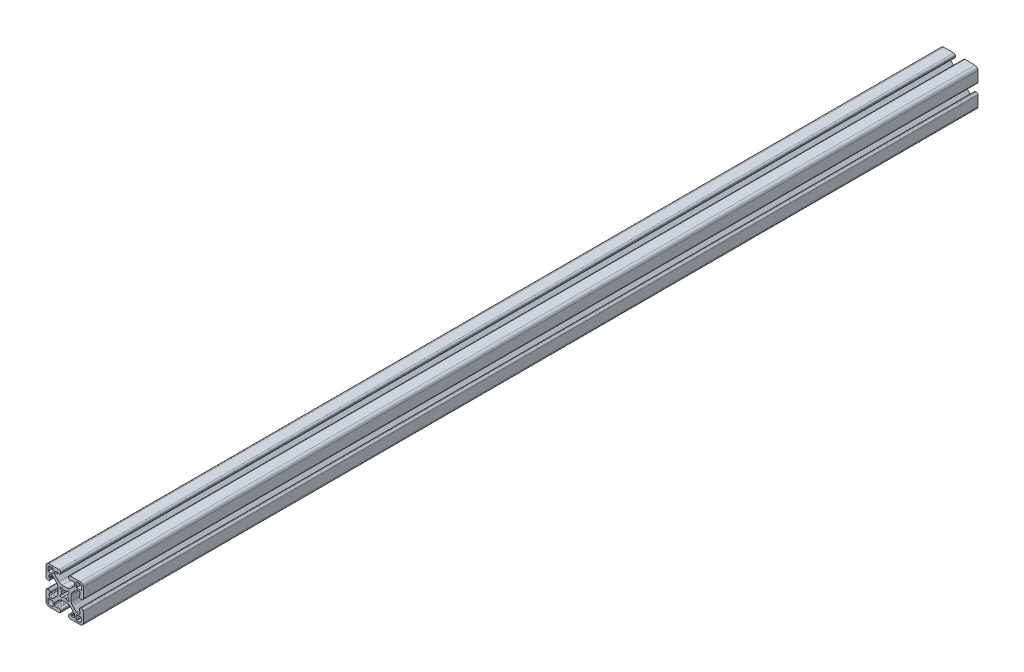
SolidWorks part; units mm, degrees
ref_plane "Front Plane" through (0, 0, 0) normal (0, 0, 1) x (1, 0, 0)
ref_plane "Top Plane" through (0, 0, 0) normal (0, 1, 0) x (1, 0, 0)
ref_plane "Right Plane" through (0, 0, 0) normal (1, 0, 0) x (0, 0, -1)
sketch "Sketch1" plane through (0, 0, 0) normal (0, 0, 1) x (1, 0, 0)
  line L0 (-66.7042, -2.4885) -> (-65.3338, -1.1181)
  line L1 (-65.3338, 1.5948) -> (-66.7042, 2.9652)
  line L2 (-65.0878, 4.5817) -> (-63.7174, 3.2112)
  line L3 (-61.0045, 3.2112) -> (-59.7212, 4.484)
  line L4 (-58.1153, 2.8781) -> (-59.388, 1.5948)
  line L5 (-59.388, -1.1181) -> (-58.0176, -2.4885)
  line L6 (-59.6341, -4.1049) -> (-61.0045, -2.7345)
  line L7 (-63.7174, -2.7345) -> (-65.0878, -4.1049)
  line L8 (-79.6076, 12.4812) -> (-79.6076, 14.691)
  line L9 (-76.8136, 17.485) -> (-74.6038, 17.485)
  line L10 (-74.2227, 17.1039) -> (-74.2227, 12.4812)
  line L11 (-74.6038, 12.1001) -> (-79.2265, 12.1001)
  line L12 (-74.6038, -17.0083) -> (-76.8136, -17.0083)
  line L13 (-79.6076, -14.2142) -> (-79.6076, -12.0045)
  line L14 (-79.2265, -11.6233) -> (-74.6038, -11.6233)
  line L15 (-74.2227, -12.0045) -> (-74.2227, -16.6272)
  line L16 (-45.1143, -12.0045) -> (-45.1143, -14.2142)
  line L17 (-47.9083, -17.0083) -> (-50.1181, -17.0083)
  line L18 (-50.4992, -16.6272) -> (-50.4992, -12.0045)
  line L19 (-50.1181, -11.6233) -> (-45.4954, -11.6233)
  line L20 (-50.1181, 17.485) -> (-47.9083, 17.485)
  line L21 (-45.1143, 14.691) -> (-45.1143, 12.4812)
  line L22 (-45.4954, 12.1001) -> (-50.1181, 12.1001)
  line L23 (-50.4992, 12.4812) -> (-50.4992, 17.1039)
  line L24 (-46.5366, -7.0008) -> (-46.5366, -8.778)
  line L25 (-47.8071, -10.0485) -> (-49.3926, -10.0485)
  line L26 (-50.291, -9.6763) -> (-54.2387, -5.7286)
  line L27 (-55.6299, -2.3699) -> (-55.6299, 2.8467)
  line L28 (-54.2387, 6.2053) -> (-50.291, 10.1531)
  line L29 (-49.3926, 10.5252) -> (-47.8071, 10.5252)
  line L30 (-46.5366, 9.2547) -> (-46.5366, 7.4775)
  line L31 (-46.9177, 7.0964) -> (-46.9939, 7.0964)
  line L32 (-47.375, 6.7153) -> (-47.375, 5.8772)
  line L33 (-45.8002, 4.3023) -> (-44.8858, 4.3023)
  line L34 (-43.3109, 5.8772) -> (-43.3109, 16.1134)
  line L35 (-46.4859, 19.2884) -> (-56.7221, 19.2884)
  line L36 (-58.297, 17.7135) -> (-58.297, 16.7991)
  line L37 (-56.7221, 15.2243) -> (-55.884, 15.2243)
  line L38 (-55.5029, 15.6054) -> (-55.5029, 15.6816)
  line L39 (-55.1218, 16.0627) -> (-53.3446, 16.0627)
  line L40 (-52.0741, 14.7922) -> (-52.0741, 13.2067)
  line L41 (-52.4462, 12.3083) -> (-56.394, 8.3605)
  line L42 (-59.7526, 6.9694) -> (-64.9692, 6.9694)
  line L43 (-68.3278, 8.3605) -> (-72.2756, 12.3083)
  line L44 (-72.6478, 13.2067) -> (-72.6478, 14.7922)
  line L45 (-71.3773, 16.0627) -> (-69.6001, 16.0627)
  line L46 (-69.219, 15.6816) -> (-69.219, 15.6054)
  line L47 (-68.8379, 15.2243) -> (-67.9997, 15.2243)
  line L48 (-66.4249, 16.7991) -> (-66.4249, 17.7135)
  line L49 (-67.9997, 19.2884) -> (-78.2359, 19.2884)
  line L50 (-81.4109, 16.1134) -> (-81.4109, 5.8772)
  line L51 (-79.8361, 4.3023) -> (-78.9217, 4.3023)
  line L52 (-77.3469, 5.8772) -> (-77.3469, 6.7153)
  line L53 (-77.728, 7.0964) -> (-77.8042, 7.0964)
  line L54 (-78.1853, 7.4775) -> (-78.1853, 9.2547)
  line L55 (-76.9148, 10.5252) -> (-75.3293, 10.5252)
  line L56 (-74.4309, 10.1531) -> (-70.4831, 6.2053)
  line L57 (-69.0919, 2.8467) -> (-69.0919, -2.3699)
  line L58 (-70.4831, -5.7286) -> (-74.4309, -9.6763)
  line L59 (-75.3293, -10.0485) -> (-76.9148, -10.0485)
  line L60 (-78.1853, -8.778) -> (-78.1853, -7.0008)
  line L61 (-77.8042, -6.6197) -> (-77.728, -6.6197)
  line L62 (-77.3469, -6.2386) -> (-77.3469, -5.4004)
  line L63 (-78.9217, -3.8256) -> (-79.8361, -3.8256)
  line L64 (-81.4109, -5.4004) -> (-81.4109, -15.6366)
  line L65 (-78.2359, -18.8117) -> (-67.9997, -18.8117)
  line L66 (-66.4249, -17.2368) -> (-66.4249, -16.3224)
  line L67 (-67.9997, -14.7476) -> (-68.8379, -14.7476)
  line L68 (-69.219, -15.1287) -> (-69.219, -15.2049)
  line L69 (-69.6001, -15.586) -> (-71.3773, -15.586)
  line L70 (-72.6478, -14.3155) -> (-72.6478, -12.73)
  line L71 (-72.2756, -11.8316) -> (-68.3278, -7.8838)
  line L72 (-64.9692, -6.4926) -> (-59.7526, -6.4926)
  line L73 (-56.394, -7.8838) -> (-52.4462, -11.8316)
  line L74 (-52.0741, -12.73) -> (-52.0741, -14.3155)
  line L75 (-53.3446, -15.586) -> (-55.1218, -15.586)
  line L76 (-55.5029, -15.2049) -> (-55.5029, -15.1287)
  line L77 (-55.884, -14.7476) -> (-56.7221, -14.7476)
  line L78 (-58.297, -16.3224) -> (-58.297, -17.2368)
  line L79 (-56.7221, -18.8117) -> (-46.4859, -18.8117)
  line L80 (-43.3109, -15.6366) -> (-43.3109, -5.4004)
  line L81 (-44.8858, -3.8256) -> (-45.8002, -3.8256)
  line L82 (-47.375, -5.4004) -> (-47.375, -6.2386)
  line L83 (-46.9939, -6.6197) -> (-46.9177, -6.6197)
  arc A0 (-66.7042, -2.4885) -> (-65.0878, -4.1049) centre (-65.896, -3.2967) ccw
  arc A1 (-65.3338, 1.5948) -> (-65.3338, -1.1181) centre (-62.3609, 0.2384) ccw
  arc A2 (-65.0878, 4.5817) -> (-66.7042, 2.9652) centre (-65.896, 3.7734) ccw
  arc A3 (-61.0045, 3.2112) -> (-63.7174, 3.2112) centre (-62.3609, 0.2384) ccw
  arc A4 (-58.1153, 2.8781) -> (-59.7212, 4.484) centre (-58.8258, 3.7734) ccw
  arc A5 (-59.388, -1.1181) -> (-59.388, 1.5948) centre (-62.3609, 0.2384) ccw
  arc A6 (-59.6341, -4.1049) -> (-58.0176, -2.4885) centre (-58.8258, -3.2967) ccw
  arc A7 (-63.7174, -2.7345) -> (-61.0045, -2.7345) centre (-62.3609, 0.2384) ccw
  arc A8 (-79.6076, 12.4812) -> (-79.2265, 12.1001) centre (-79.2265, 12.4812) ccw
  arc A9 (-76.8136, 17.485) -> (-79.6076, 14.691) centre (-76.8136, 14.691) ccw
  arc A10 (-74.2227, 17.1039) -> (-74.6038, 17.485) centre (-74.6038, 17.1039) ccw
  arc A11 (-74.6038, 12.1001) -> (-74.2227, 12.4812) centre (-74.6038, 12.4812) ccw
  arc A12 (-74.6038, -17.0083) -> (-74.2227, -16.6272) centre (-74.6038, -16.6272) ccw
  arc A13 (-79.6076, -14.2142) -> (-76.8136, -17.0083) centre (-76.8136, -14.2142) ccw
  arc A14 (-79.2265, -11.6233) -> (-79.6076, -12.0045) centre (-79.2265, -12.0045) ccw
  arc A15 (-74.2227, -12.0045) -> (-74.6038, -11.6233) centre (-74.6038, -12.0045) ccw
  arc A16 (-45.1143, -12.0045) -> (-45.4954, -11.6233) centre (-45.4954, -12.0045) ccw
  arc A17 (-47.9083, -17.0083) -> (-45.1143, -14.2142) centre (-47.9083, -14.2142) ccw
  arc A18 (-50.4992, -16.6272) -> (-50.1181, -17.0083) centre (-50.1181, -16.6272) ccw
  arc A19 (-50.1181, -11.6233) -> (-50.4992, -12.0045) centre (-50.1181, -12.0045) ccw
  arc A20 (-50.1181, 17.485) -> (-50.4992, 17.1039) centre (-50.1181, 17.1039) ccw
  arc A21 (-45.1143, 14.691) -> (-47.9083, 17.485) centre (-47.9083, 14.691) ccw
  arc A22 (-45.4954, 12.1001) -> (-45.1143, 12.4812) centre (-45.4954, 12.4812) ccw
  arc A23 (-50.4992, 12.4812) -> (-50.1181, 12.1001) centre (-50.1181, 12.4812) ccw
  arc A24 (-47.8071, -10.0485) -> (-46.5366, -8.778) centre (-47.8071, -8.778) ccw
  arc A25 (-50.291, -9.6763) -> (-49.3926, -10.0485) centre (-49.3926, -8.778) ccw
  arc A26 (-55.6299, -2.3699) -> (-54.2387, -5.7286) centre (-50.8801, -2.3699) ccw
  arc A27 (-54.2387, 6.2053) -> (-55.6299, 2.8467) centre (-50.8801, 2.8467) ccw
  arc A28 (-49.3926, 10.5252) -> (-50.291, 10.1531) centre (-49.3926, 9.2547) ccw
  arc A29 (-46.5366, 9.2547) -> (-47.8071, 10.5252) centre (-47.8071, 9.2547) ccw
  arc A30 (-46.9177, 7.0964) -> (-46.5366, 7.4775) centre (-46.9177, 7.4775) ccw
  arc A31 (-46.9939, 7.0964) -> (-47.375, 6.7153) centre (-46.9939, 6.7153) ccw
  arc A32 (-47.375, 5.8772) -> (-45.8002, 4.3023) centre (-45.8002, 5.8772) ccw
  arc A33 (-44.8858, 4.3023) -> (-43.3109, 5.8772) centre (-44.8858, 5.8772) ccw
  arc A34 (-43.3109, 16.1134) -> (-46.4859, 19.2884) centre (-46.4859, 16.1134) ccw
  arc A35 (-56.7221, 19.2884) -> (-58.297, 17.7135) centre (-56.7221, 17.7135) ccw
  arc A36 (-58.297, 16.7991) -> (-56.7221, 15.2243) centre (-56.7221, 16.7991) ccw
  arc A37 (-55.884, 15.2243) -> (-55.5029, 15.6054) centre (-55.884, 15.6054) ccw
  arc A38 (-55.1218, 16.0627) -> (-55.5029, 15.6816) centre (-55.1218, 15.6816) ccw
  arc A39 (-52.0741, 14.7922) -> (-53.3446, 16.0627) centre (-53.3446, 14.7922) ccw
  arc A40 (-52.4462, 12.3083) -> (-52.0741, 13.2067) centre (-53.3446, 13.2067) ccw
  arc A41 (-59.7526, 6.9694) -> (-56.394, 8.3605) centre (-59.7526, 11.7192) ccw
  arc A42 (-68.3278, 8.3605) -> (-64.9692, 6.9694) centre (-64.9692, 11.7192) ccw
  arc A43 (-72.6478, 13.2067) -> (-72.2756, 12.3083) centre (-71.3773, 13.2067) ccw
  arc A44 (-71.3773, 16.0627) -> (-72.6478, 14.7922) centre (-71.3773, 14.7922) ccw
  arc A45 (-69.219, 15.6816) -> (-69.6001, 16.0627) centre (-69.6001, 15.6816) ccw
  arc A46 (-69.219, 15.6054) -> (-68.8379, 15.2243) centre (-68.8379, 15.6054) ccw
  arc A47 (-67.9997, 15.2243) -> (-66.4249, 16.7991) centre (-67.9997, 16.7991) ccw
  arc A48 (-66.4249, 17.7135) -> (-67.9997, 19.2884) centre (-67.9997, 17.7135) ccw
  arc A49 (-78.2359, 19.2884) -> (-81.4109, 16.1134) centre (-78.2359, 16.1134) ccw
  arc A50 (-81.4109, 5.8772) -> (-79.8361, 4.3023) centre (-79.8361, 5.8772) ccw
  arc A51 (-78.9217, 4.3023) -> (-77.3469, 5.8772) centre (-78.9217, 5.8772) ccw
  arc A52 (-77.3469, 6.7153) -> (-77.728, 7.0964) centre (-77.728, 6.7153) ccw
  arc A53 (-78.1853, 7.4775) -> (-77.8042, 7.0964) centre (-77.8042, 7.4775) ccw
  arc A54 (-76.9148, 10.5252) -> (-78.1853, 9.2547) centre (-76.9148, 9.2547) ccw
  arc A55 (-74.4309, 10.1531) -> (-75.3293, 10.5252) centre (-75.3293, 9.2547) ccw
  arc A56 (-69.0919, 2.8467) -> (-70.4831, 6.2053) centre (-73.8417, 2.8467) ccw
  arc A57 (-70.4831, -5.7286) -> (-69.0919, -2.3699) centre (-73.8417, -2.3699) ccw
  arc A58 (-75.3293, -10.0485) -> (-74.4309, -9.6763) centre (-75.3293, -8.778) ccw
  arc A59 (-78.1853, -8.778) -> (-76.9148, -10.0485) centre (-76.9148, -8.778) ccw
  arc A60 (-77.8042, -6.6197) -> (-78.1853, -7.0008) centre (-77.8042, -7.0008) ccw
  arc A61 (-77.728, -6.6197) -> (-77.3469, -6.2386) centre (-77.728, -6.2386) ccw
  arc A62 (-77.3469, -5.4004) -> (-78.9217, -3.8256) centre (-78.9217, -5.4004) ccw
  arc A63 (-79.8361, -3.8256) -> (-81.4109, -5.4004) centre (-79.8361, -5.4004) ccw
  arc A64 (-81.4109, -15.6366) -> (-78.2359, -18.8117) centre (-78.2359, -15.6366) ccw
  arc A65 (-67.9997, -18.8117) -> (-66.4249, -17.2368) centre (-67.9997, -17.2368) ccw
  arc A66 (-66.4249, -16.3224) -> (-67.9997, -14.7476) centre (-67.9997, -16.3224) ccw
  arc A67 (-68.8379, -14.7476) -> (-69.219, -15.1287) centre (-68.8379, -15.1287) ccw
  arc A68 (-69.6001, -15.586) -> (-69.219, -15.2049) centre (-69.6001, -15.2049) ccw
  arc A69 (-72.6478, -14.3155) -> (-71.3773, -15.586) centre (-71.3773, -14.3155) ccw
  arc A70 (-72.2756, -11.8316) -> (-72.6478, -12.73) centre (-71.3773, -12.73) ccw
  arc A71 (-64.9692, -6.4926) -> (-68.3278, -7.8838) centre (-64.9692, -11.2424) ccw
  arc A72 (-56.394, -7.8838) -> (-59.7526, -6.4926) centre (-59.7526, -11.2424) ccw
  arc A73 (-52.0741, -12.73) -> (-52.4462, -11.8316) centre (-53.3446, -12.73) ccw
  arc A74 (-53.3446, -15.586) -> (-52.0741, -14.3155) centre (-53.3446, -14.3155) ccw
  arc A75 (-55.5029, -15.2049) -> (-55.1218, -15.586) centre (-55.1218, -15.2049) ccw
  arc A76 (-55.5029, -15.1287) -> (-55.884, -14.7476) centre (-55.884, -15.1287) ccw
  arc A77 (-56.7221, -14.7476) -> (-58.297, -16.3224) centre (-56.7221, -16.3224) ccw
  arc A78 (-58.297, -17.2368) -> (-56.7221, -18.8117) centre (-56.7221, -17.2368) ccw
  arc A79 (-46.4859, -18.8117) -> (-43.3109, -15.6366) centre (-46.4859, -15.6366) ccw
  arc A80 (-43.3109, -5.4004) -> (-44.8858, -3.8256) centre (-44.8858, -5.4004) ccw
  arc A81 (-45.8002, -3.8256) -> (-47.375, -5.4004) centre (-45.8002, -5.4004) ccw
  arc A82 (-47.375, -6.2386) -> (-46.9939, -6.6197) centre (-46.9939, -6.2386) ccw
  arc A83 (-46.5366, -7.0008) -> (-46.9177, -6.6197) centre (-46.9177, -7.0008) ccw
  dimension "D1" = 58.1153
  dimension "D2" = 59.7212
extrude "Extrude1" add sketch "Sketch1" against normal blind 914.4
